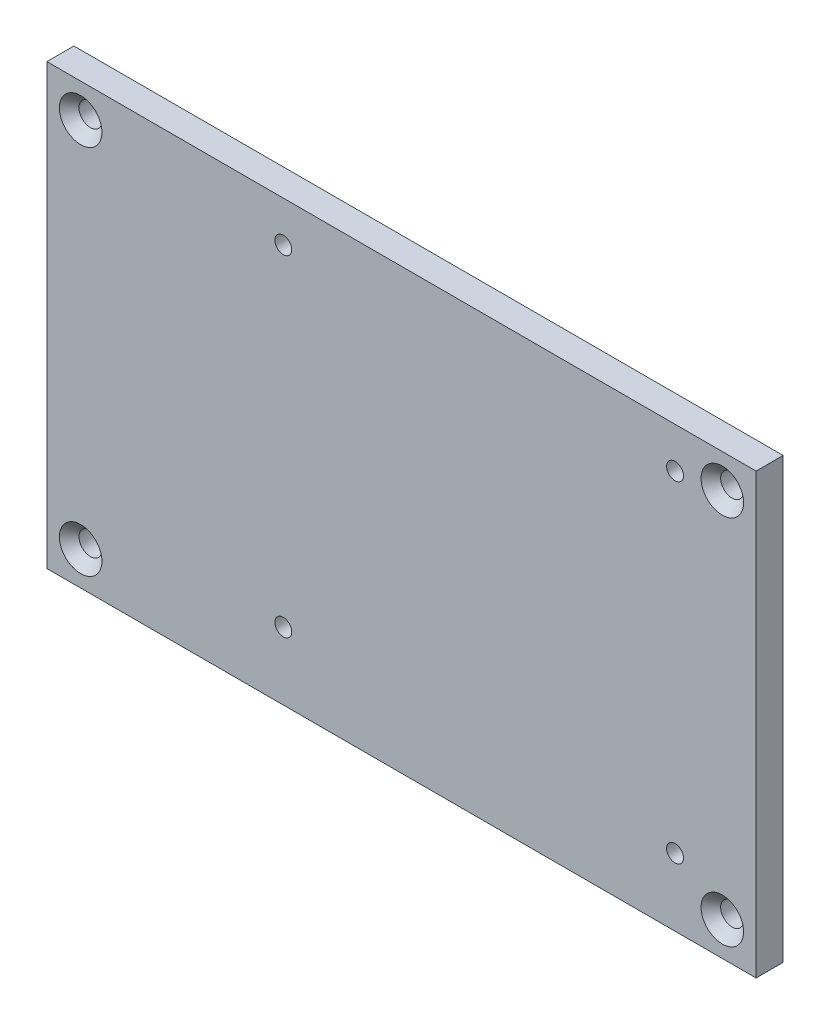
SolidWorks part; units mm, degrees
ref_plane "前基準面" through (0, 0, 0) normal (0, 0, 1) x (1, 0, 0)
ref_plane "上基準面" through (0, 0, 0) normal (0, 1, 0) x (1, 0, 0)
ref_plane "右基準面" through (0, 0, 0) normal (1, 0, 0) x (0, 0, -1)
sketch "草圖1" plane through (0, 0, 0) normal (0, 0, 1) x (1, 0, 0)
  line L1 (-52.5, -32.5) -> (52.5, -32.5)
  line L2 (-52.5, -32.5) -> (-52.5, 32.5)
  line L3 (-52.5, 32.5) -> (52.5, 32.5)
  line L4 (52.5, -32.5) -> (52.5, 32.5)
  line L5 (-52.5, -32.5) -> (52.5, 32.5) construction
  line L6 (-52.5, 32.5) -> (52.5, -32.5) construction
  point P0 (0, 0)
  dimension "D1" = 105
  dimension "D2" = 65
extrude "填料-伸長1" add sketch "草圖1" along normal blind 4
hole_wizard "M3 螺紋孔1" positions "草圖2" profile "草圖4" tap size "M3" standard "ISO" end condition through all
sketch "草圖2" plane through (0, 0, 4) normal (0, 0, 1) x (1, 0, 0)
  line L1 (-17.5, -22.5) -> (40.5, -22.5)
  line L2 (-17.5, -22.5) -> (-17.5, 26.5)
  line L3 (-17.5, 26.5) -> (40.5, 26.5)
  line L4 (40.5, -22.5) -> (40.5, 26.5)
  line L5 (-17.5, -22.5) -> (40.5, 26.5) construction
  line L6 (-17.5, 26.5) -> (40.5, -22.5) construction
  line L7 (-52.5, -32.5) -> (52.5, -32.5) construction
  line L8 (52.5, -32.5) -> (52.5, 32.5) construction
  point P0 (40.5, 26.5)
  point P2 (40.5, -22.5)
  point P4 (-17.5, -22.5)
  point P6 (-17.5, 26.5)
  point P97 (0, 0)
  point P98 (0, 0)
  point P99 (0, 0)
  point P100 (0, 0)
  point P101 (0, 0)
  dimension "D1" = 49
  dimension "D2" = 58
  dimension "D3" = 10
  dimension "D4" = 12
sketch "草圖4" plane through (40.5, 26.5, 4) normal (1, 0, 0) x (0, -1, 0)
  line L0 (0, 0) -> (0, 4)
  line L1 (0, 4) -> (1.25, 4)
  line L2 (1.25, 4) -> (1.25, 0)
  line L5 (1.25, 0) -> (0, 0)
  line L11 (0, -6.35) -> (0, 107.95) construction
  dimension "貫穿螺孔鑽直徑" = 2.5
  dimension "貫穿螺孔鑽深度" = 4
cosmetic thread "鑽孔螺紋1"
cosmetic thread "鑽孔螺紋2"
cosmetic thread "鑽孔螺紋3"
cosmetic thread "鑽孔螺紋4"
hole_wizard "M3 錐坑平頭螺釘的錐孔1" positions "草圖5" profile "草圖6" countersink size "M3" standard "ISO" end condition through all
sketch "草圖5" plane through (0, 0, 4) normal (0, 0, 1) x (1, 0, 0)
  line L0 (52.5, 32.5) -> (-52.5, 32.5) construction
  line L1 (52.5, -32.5) -> (52.5, 32.5) construction
  line L2 (-52.5, 32.5) -> (-52.5, -32.5) construction
  line L3 (-52.5, -32.5) -> (52.5, -32.5) construction
  point P0 (-47.5, 27.5)
  point P2 (-47.5, -27.5)
  point P4 (47.5, 27.5)
  point P6 (47.5, -27.5)
  point P9 (0, 0)
  point P10 (0, 0)
  point P11 (0, 0)
  dimension "D1" = 5
  dimension "D2" = 5
  dimension "D3" = 5
  dimension "D4" = 5
sketch "草圖6" plane through (-47.5, 27.5, 4) normal (1, 0, 0) x (0, -1, 0)
  line L0 (0, 0) -> (0, 4)
  line L1 (0, 4) -> (1.7, 4)
  line L2 (1.7, 4) -> (1.7, 1.45)
  line L3 (1.7, 1.45) -> (3.15, 0)
  line L5 (3.15, 0) -> (0, 0)
  line L6 (-1.7, 1.45) -> (-3.15, 0) construction
  line L11 (0, -6.35) -> (0, 107.95) construction
  dimension "貫穿孔直徑" = 3.4
  dimension "貫穿孔深度" = 4
  dimension "近端錐孔直徑" = 6.3
  dimension "近端錐孔角度" = 90
